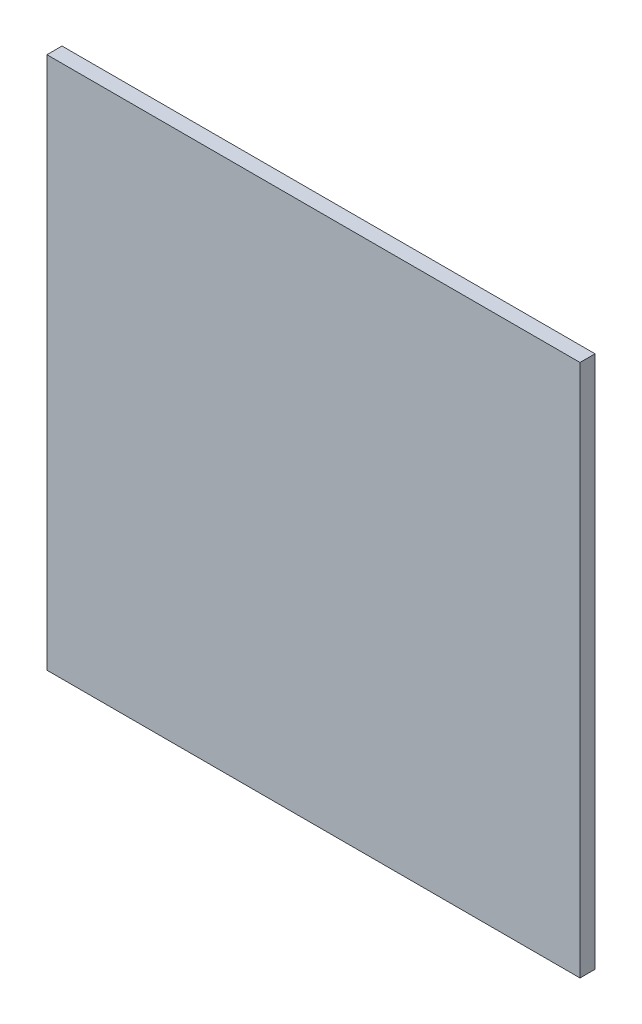
SolidWorks part; units mm, degrees
ref_plane "Plano frontal" through (0, 0, 0) normal (0, 0, 1) x (1, 0, 0)
ref_plane "Plano superior" through (0, 0, 0) normal (0, 1, 0) x (1, 0, 0)
ref_plane "Plano direito" through (0, 0, 0) normal (1, 0, 0) x (0, 0, -1)
sketch "Esboço1" plane through (0, 0, 0) normal (0, 0, 1) x (1, 0, 0)
  line L0 (177, 177) -> (-177, -177) construction
  line L1 (-177, 177) -> (177, 177)
  line L2 (-177, 177) -> (-177, -177)
  line L3 (-177, -177) -> (177, -177)
  line L4 (177, 177) -> (177, -177)
  dimension "D1" = 354
  dimension "D2" = 354
extrude "Ressalto-extrusão1" add sketch "Esboço1" along normal blind 10
